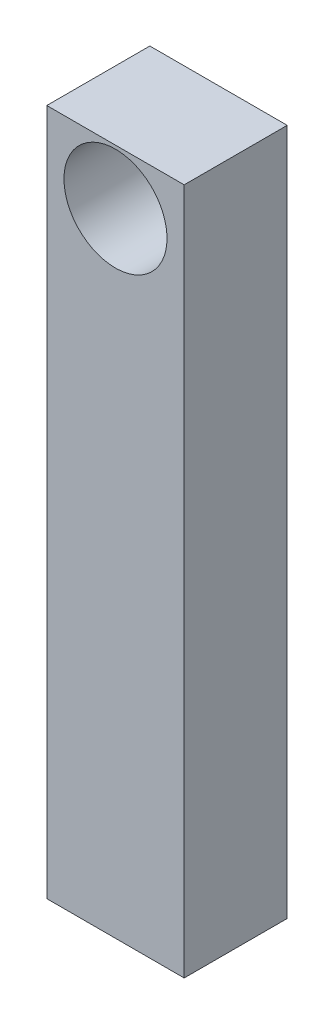
SolidWorks part; units mm, degrees
ref_plane "前基準面" through (0, 0, 0) normal (0, 0, 1) x (1, 0, 0)
ref_plane "上基準面" through (0, 0, 0) normal (0, 1, 0) x (1, 0, 0)
ref_plane "右基準面" through (0, 0, 0) normal (1, 0, 0) x (0, 0, -1)
sketch "草圖1" plane through (0, 0, 0) normal (0, 0, 1) x (1, 0, 0)
  line L1 (-2, 10) -> (2, 10)
  line L2 (-2, 10) -> (-2, -10)
  line L3 (-2, -10) -> (2, -10)
  line L4 (2, 10) -> (2, -10)
  line L5 (-2, 10) -> (2, -10) construction
  line L6 (-2, -10) -> (2, 10) construction
  point P0 (0, 0)
  dimension "D1" = 4
  dimension "D2" = 20
extrude "填料-伸長1" add sketch "草圖1" along normal blind 3
sketch "草圖2" plane through (0, 0, 0) normal (0, 0, -1) x (-1, 0, 0)
  line L0 (-2, 10) -> (2, 10) construction
  circle A0 centre (0, 8.4) radius 1.5
  point P2 (0, 10)
  dimension "D1" = 3
  dimension "D2" = 1.6
extrude "除料-伸長3" cut sketch "草圖2" against normal blind 3
